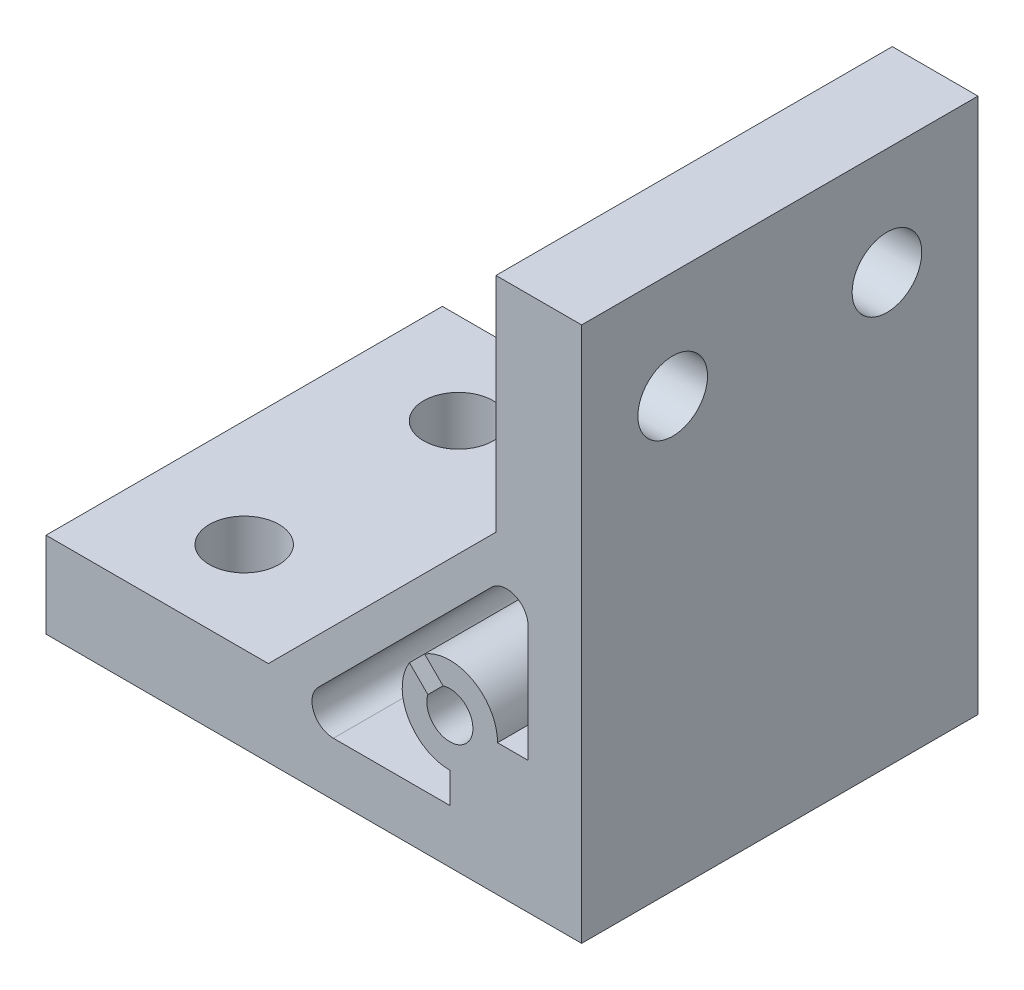
SolidWorks part; units mm, degrees
ref_plane "前视基准面" through (0, 0, 0) normal (0, 0, 1) x (1, 0, 0)
ref_plane "上视基准面" through (0, 0, 0) normal (0, 1, 0) x (1, 0, 0)
ref_plane "右视基准面" through (0, 0, 0) normal (1, 0, 0) x (0, 0, -1)
sketch "草图1" plane through (0, 0, 0) normal (0, 0, 1) x (1, 0, 0)
  line B0 (0, 0) -> (50, 0)
  line B1 (50, 0) -> (50, 50)
  line B2 (0, 8) -> (20.7574, 8)
  line B3 (42, 29.2426) -> (42, 50)
  line B4 (0, 8) -> (0, 0)
  line B5 (42, 50) -> (50, 50)
  line B6 (37.0613, 14.3529) -> (35.341, 16.0733)
  line B7 (35.6471, 12.9387) -> (33.9267, 14.659)
  line B8 (25.4142, 8.4142) -> (41.5858, 24.5858)
  line B9 (20.7574, 8) -> (42, 29.2426)
  line B10 (26.8284, 5) -> (37.7, 5)
  line B11 (45, 23.1716) -> (45, 12.3)
  line B12 (37.7, 5) -> (37.7, 7.85)
  line B13 (42.15, 12.3) -> (45, 12.3)
  arc B14 (33.9267, 14.659) -> (37.7, 7.85) centre (37.7, 12.3) ccw
  arc B15 (42.15, 12.3) -> (35.341, 16.0733) centre (37.7, 12.3) ccw
  arc B16 (35.6471, 12.9387) -> (37.0613, 14.3529) centre (37.7, 12.3) ccw
  arc B17 (25.4142, 8.4142) -> (26.8284, 5) centre (26.8284, 7) ccw
  arc B18 (45, 23.1716) -> (41.5858, 24.5858) centre (43, 23.1716) ccw
sketch_block_instance "A$C19004297-1"
sketch_block "A$C19004297"
extrude "凸台-拉伸1" add sketch "草图1" along normal mid plane 37
sketch "草图3" plane through (0, 8, 0) normal (0, 1, 0) x (1, 0, 0)
  line L0 (0, 0) -> (20.0952, 0) construction
  line L1 (0, -18.5) -> (0, 18.5) construction
  circle A0 centre (10, 10) radius 3.25
  circle A1 centre (10, -10) radius 3.25
  dimension "D1" = 10
  dimension "D2" = 10
extrude "切除-拉伸1" cut sketch "草图3" against normal through all
sketch "草图4" plane through (6.3787, -6.3787, 0) normal (-0.7071, 0.7071, 0) x (0, 0, 1)
  line L0 (18.5, 35.3553) -> (-18.5, 35.3553) construction
  line L1 (18.5, 50.3762) -> (18.5, 20.3345) construction
  line L2 (-18.5, 50.3762) -> (-18.5, 20.3345) construction
ref_plane "基准面2" through (25, 25, 0) normal (-0.7071, -0.7071, 0) x (0, 0, 1)
mirror "镜向1" about plane through (25, 25, 0) normal (-0.7071, -0.7071, 0) of "切除-拉伸1"
